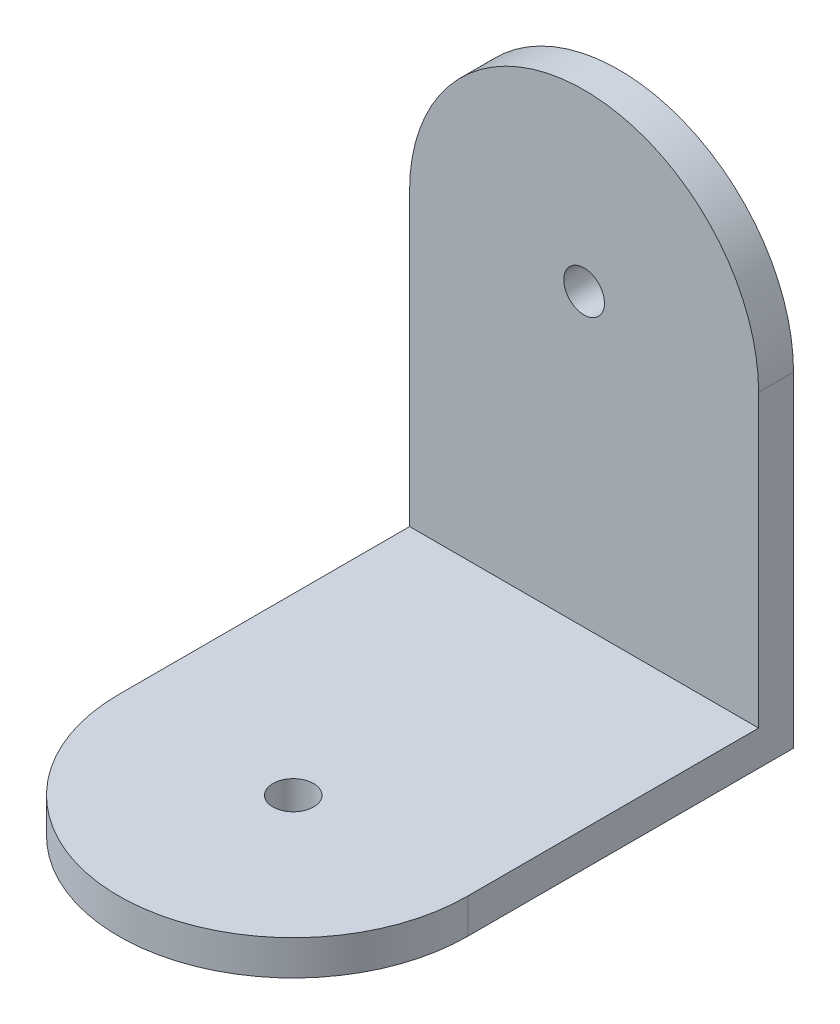
SolidWorks part; units mm, degrees
ref_plane "Plano frontal" through (0, 0, 0) normal (0, 0, 1) x (1, 0, 0)
ref_plane "Plano superior" through (0, 0, 0) normal (0, 1, 0) x (1, 0, 0)
ref_plane "Plano direito" through (0, 0, 0) normal (1, 0, 0) x (0, 0, -1)
sketch "Esboço1" plane through (0, 0, 0) normal (0, 0, 1) x (1, 0, 0)
  line L0 (0, -20.8884) -> (0, 32.1694) construction
  line L1 (-15, 11.3572) -> (-15, -13.6428)
  line L6 (15, 11.3572) -> (15, -13.6428)
  line L7 (-15, -13.6428) -> (15, -13.6428)
  line L9 (-15, -13.6428) -> (15, -13.6428)
  line L10 (-15, -13.6428) -> (-15, -16.6428)
  line L11 (-15, -16.6428) -> (15, -16.6428)
  line L12 (15, -13.6428) -> (15, -16.6428)
  arc A0 (-15, 11.3572) -> (15, 11.3572) centre (0, 11.3572) cw
  circle A1 centre (0, 11.3572) radius 1.75
  point P4 (0, 26.3572)
  dimension "D1" = 30
  dimension "D2" = 15
  dimension "D3" = 3
  dimension "D4" = 40
extrude "Ressalto-extrusão1" add sketch "Esboço1" along normal blind 3 contours L0 L9 L6 A0 | L7 L0 A0 L1
sketch "Esboço2" plane through (0, 0, 0) normal (0, 0, -1) x (-1, 0, 0)
  line L1 (-15, -13.6428) -> (15, -13.6428)
  line L2 (-15, -13.6428) -> (-15, -16.6428)
  line L3 (-15, -16.6428) -> (15, -16.6428)
  line L4 (15, -13.6428) -> (15, -16.6428)
extrude "Ressalto-extrusão2" add sketch "Esboço2" against normal blind 43
sketch "Esboço3" plane through (0, -13.6428, 0) normal (0, 1, 0) x (1, 0, 0)
  line L0 (15, -28) -> (15, -43)
  line L1 (15, -43) -> (-15, -43)
  line L2 (-15, -43) -> (-15, -28)
  line L3 (0, -3) -> (0, -28) construction
  line L6 (-15, -3) -> (15, -3) construction
  line L7 (-15, -43) -> (-15, -3) construction
  line L8 (15, -43) -> (15, -3) construction
  arc A0 (-15, -28) -> (15, -28) centre (0, -28) ccw
  line M3 (-15, -3) -> (-15, -43)
  line M4 (-15, -43) -> (15, -43)
  line M5 (15, -43) -> (15, -3)
extrude "Corte-extrusão1" cut sketch "Esboço3" against normal through all and the other way through all contours A0 L1 M5 | A0 M3 M4
sketch "Esboço4" plane through (0, -13.6428, 0) normal (0, 1, 0) x (1, 0, 0)
  circle A0 centre (0, -28) radius 1.75
extrude "Corte-extrusão2" cut sketch "Esboço4" against normal through all
